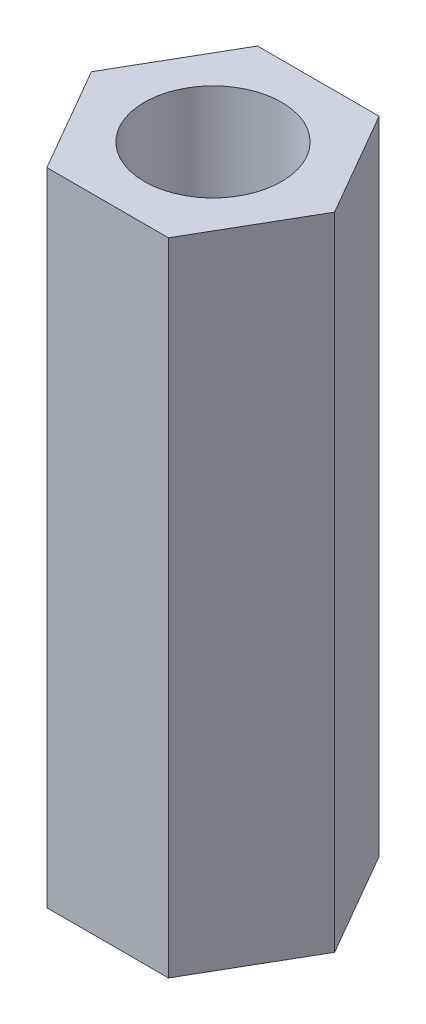
SolidWorks part; units mm, degrees
material "黄铜"
ref_plane "前视基准面" through (0, 0, 0) normal (0, 0, 1) x (1, 0, 0)
ref_plane "上视基准面" through (0, 0, 0) normal (0, 1, 0) x (1, 0, 0)
ref_plane "右视基准面" through (0, 0, 0) normal (1, 0, 0) x (0, 0, -1)
sketch "草图1" plane through (0, 0, 0) normal (0, 1, 0) x (1, 0, 0)
  line L1 (2.6558, 0) -> (1.3279, 2.3)
  line L2 (1.3279, 2.3) -> (-1.3279, 2.3)
  line L3 (-1.3279, 2.3) -> (-2.6558, 0)
  line L4 (-2.6558, 0) -> (-1.3279, -2.3)
  line L5 (-1.3279, -2.3) -> (1.3279, -2.3)
  line L6 (1.3279, -2.3) -> (2.6558, 0)
  circle A0 centre (0, 0) radius 2.3 construction
  dimension "D1" = 4.6
extrude "凸台-拉伸1" add sketch "草图1" along normal blind 14
sketch "草图2" plane through (0, 14, 0) normal (0, 1, 0) x (1, 0, 0)
  point P0 (0, 0)
hole_wizard "孔1" positions "草图2" profile "草图3" legacy end condition through all
sketch "草图3" plane through (0, 14, 0) normal (1, 0, 0) x (0, 0, 1)
  line L0 (0, 0) -> (0, 14)
  line L1 (0, 14) -> (1.5, 14)
  line L2 (1.5, 14) -> (1.5, 0)
  line L3 (1.5, 0) -> (0, 0)
  line L4 (0, 110) -> (0, -10) construction
  dimension "直径" = 3
  dimension "深度" = 14
